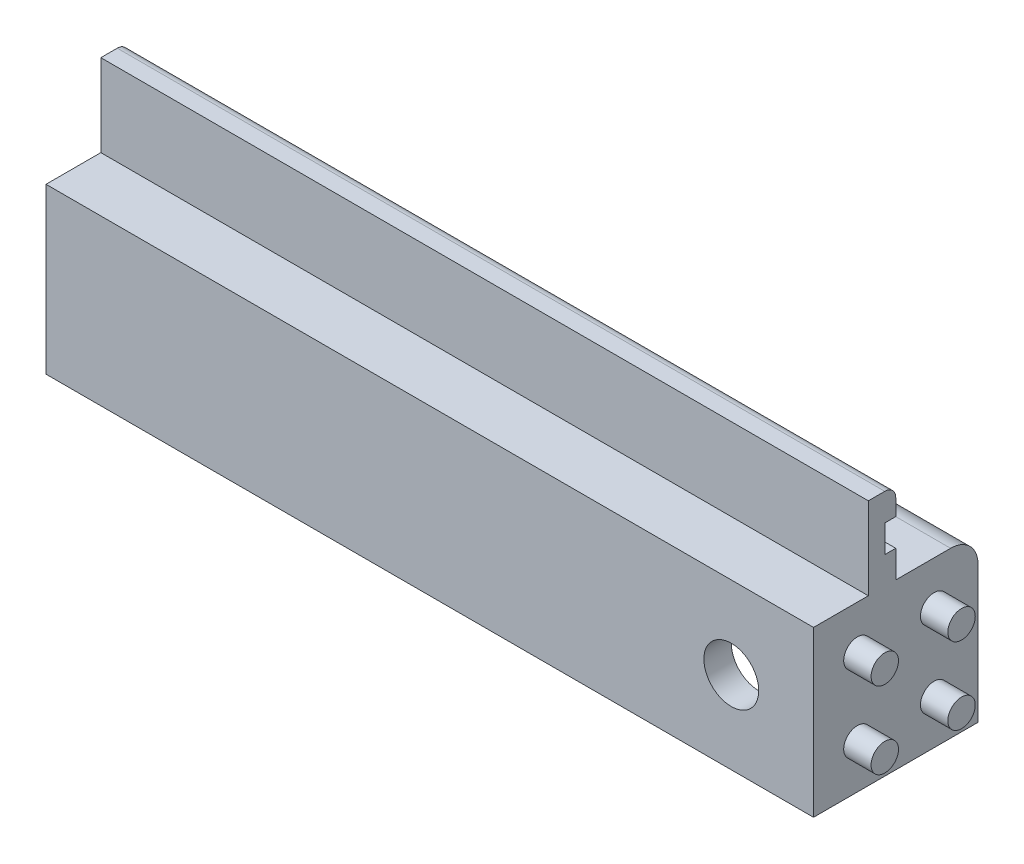
SolidWorks part; units mm, degrees
ref_plane "Front Plane" through (0, 0, 0) normal (0, 0, 1) x (1, 0, 0)
ref_plane "Top Plane" through (0, 0, 0) normal (0, 1, 0) x (1, 0, 0)
ref_plane "Right Plane" through (0, 0, 0) normal (1, 0, 0) x (0, 0, -1)
sketch "Sketch1" plane through (0, 0, 0) normal (0, 1, 0) x (1, 0, 0)
  line L0 (0, 0) -> (140, 0)
  line L1 (140, 0) -> (140, 30)
  line L2 (140, 30) -> (0, 30)
  line L3 (0, 30) -> (0, 0)
  dimension "D1" = 140
  dimension "D2" = 30
extrude "Boss-Extrude1" add sketch "Sketch1" along normal blind 30
shell "Shell1" thickness 5
sketch "Sketch3" plane through (0, 25, 0) normal (0, -1, 0) x (1, 0, 0)
  line L0 (50, -5) -> (50, -25)
  line L1 (5, -5) -> (135, -5) construction
  line L2 (135, -25) -> (5, -25) construction
  line L3 (50, -25) -> (55, -25)
  line L4 (55, -25) -> (55, -5)
  line L5 (55, -5) -> (50, -5)
  line L6 (5, -25) -> (5, -5) construction
  dimension "D1" = 5
  dimension "D2" = 45
extrude "Boss-Extrude2" add sketch "Sketch3" along normal blind 25
sketch "Sketch4" plane through (140, 0, 0) normal (1, 0, 0) x (0, 0, -1)
  line L0 (0, 30) -> (0, 0) construction
  line L1 (0, 30) -> (30, 30) construction
  line L2 (30, 30) -> (30, 0) construction
  line L3 (0, 0) -> (30, 0) construction
  circle A0 centre (8, 22) radius 2.5
  circle A1 centre (22, 22) radius 2.5
  circle A2 centre (8, 8) radius 2.5
  circle A3 centre (22, 8) radius 2.5
  dimension "D3" = 5
  dimension "D1" = 8
  dimension "D2" = 8
  dimension "D4" = 8
  dimension "D5" = 8
extrude "Boss-Extrude3" add sketch "Sketch4" along normal blind 5
sketch "Sketch5" plane through (0, 0, 0) normal (-1, 0, 0) x (0, 0, 1)
  line L0 (-30, 0) -> (0, 0) construction
  line L1 (-15, 30) -> (-15, 0) construction
  line L2 (-30, 30) -> (0, 30) construction
  circle A1 centre (-15, 15) radius 1.5
  point P6 (-15, 0)
  point P12 (-15, 15)
  dimension "D1" = 3
extrude "Cut-Extrude1" cut sketch "Sketch5" against normal blind 20
sketch "Sketch9" plane through (0, 0, -30) normal (0, 0, -1) x (-1, 0, 0)
  line L0 (-140, 30) -> (-140, 0) construction
  line L2 (-125, 0) -> (-125, 30) construction
  line L3 (-140, 0) -> (0, 0) construction
  line L4 (-140, 30) -> (0, 30) construction
  circle A1 centre (-125, 15) radius 5
  point P11 (-125, 15)
  dimension "D2" = 10
  dimension "D1" = 15
extrude "Cut-Extrude2" cut sketch "Sketch9" against normal through all both and the other way through all
sketch "Sketch10" plane through (0, 30, 0) normal (0, 1, 0) x (1, 0, 0)
  line L0 (140, 0) -> (140, 30) construction
  line L1 (0, 15) -> (140, 15)
  line L2 (0, 15) -> (0, 10)
  line L3 (0, 10) -> (140, 10)
  line L4 (140, 15) -> (140, 10)
  line L5 (0, 0) -> (140, 0) construction
  dimension "D1" = 10
  dimension "D2" = 5
extrude "Boss-Extrude5" add sketch "Sketch10" along normal blind 15
sketch "Sketch14" plane through (0, 0, -10) normal (0, 0, 1) x (1, 0, 0)
  line L0 (0, 30) -> (140, 30) construction
  line L1 (140, 40) -> (5, 40)
  line L2 (140, 40) -> (140, 35)
  line L3 (140, 35) -> (5, 35)
  line L4 (5, 40) -> (5, 35)
  line L7 (140, 45) -> (140, 30) construction
  line L8 (0, 45) -> (0, 30) construction
  dimension "D1" = 5
  dimension "D2" = 5
  dimension "D3" = 5
extrude "Cut-Extrude3" cut sketch "Sketch14" against normal blind 2 from offset 3 offset against normal yes
fillet "Fillet1" radius 2 1 edges at (70, 45, -15)
hole_wizard "CSK for M5 Flat Head Machine Screw1" positions "Sketch15" profile "Sketch16" countersink size "M5" standard "ANSI Metric"
sketch "Sketch15" plane through (0, 0, 0) normal (-1, 0, 0) x (0, 0, 1)
  point P0 (-15, 15)
sketch "Sketch16" plane through (0, 15, -15) normal (0, 1, 0) x (0, 0, 1)
  line L0 (0, 0) -> (0, 21.6524)
  line L1 (0, 21.6524) -> (2.75, 20)
  line L2 (2.75, 20) -> (2.75, 2.45)
  line L3 (2.75, 2.45) -> (5.2, 0)
  line L5 (5.2, 0) -> (0, 0)
  line L6 (-2.75, 2.45) -> (-5.2, 0) construction
  line L10 (0, 21.6524) -> (-2.75, 20) construction
  line L11 (0, -6.35) -> (0, 107.95) construction
  dimension "Hole Dia." = 5.5
  dimension "Hole Depth" = 20
  dimension "Near C'Sink Dia." = 10.4
  dimension "Near C'Sink Angle" = 90
  dimension "Drill Angle" = 118
fillet "Fillet2" radius 5 1 edges at (70, 30, -30)
